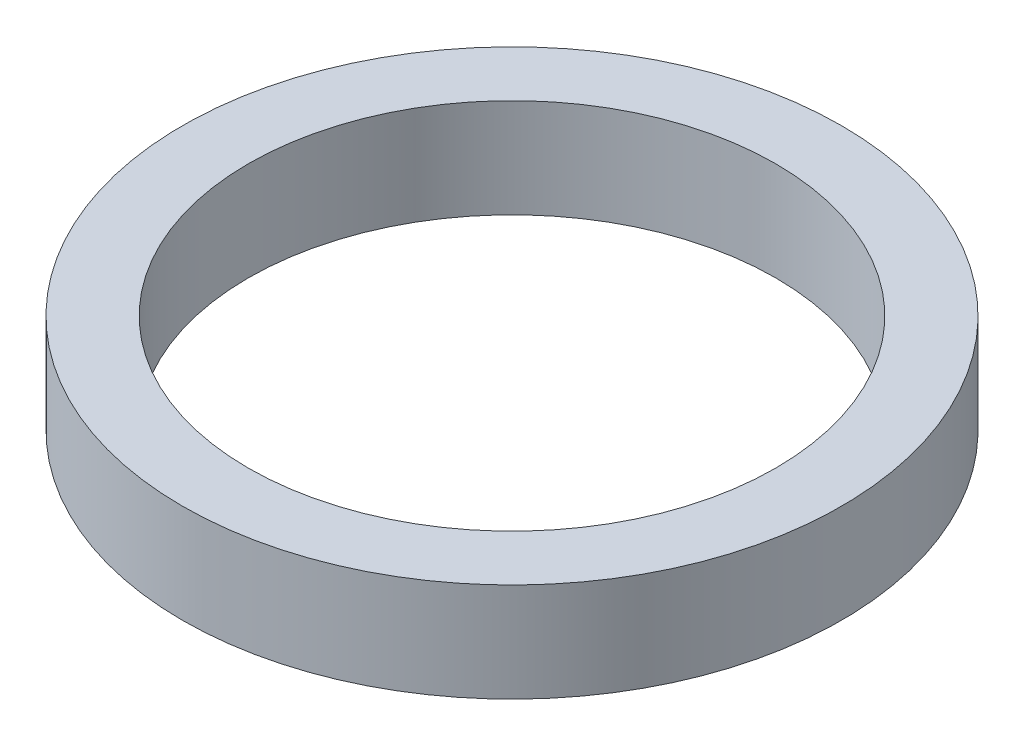
SolidWorks part; units mm, degrees
ref_plane "Front Plane" through (0, 0, 0) normal (0, 0, 1) x (1, 0, 0)
ref_plane "Top Plane" through (0, 0, 0) normal (0, 1, 0) x (1, 0, 0)
ref_plane "Right Plane" through (0, 0, 0) normal (1, 0, 0) x (0, 0, -1)
sketch "Sketch1" plane through (0, 0, 0) normal (0, 1, 0) x (1, 0, 0)
  circle A0 centre (0, 0) radius 4
  circle A1 centre (0, 0) radius 5
  dimension "D2" = 8
  dimension "D1" = 1
extrude "Boss-Extrude1" add sketch "Sketch1" along normal blind 1.5
